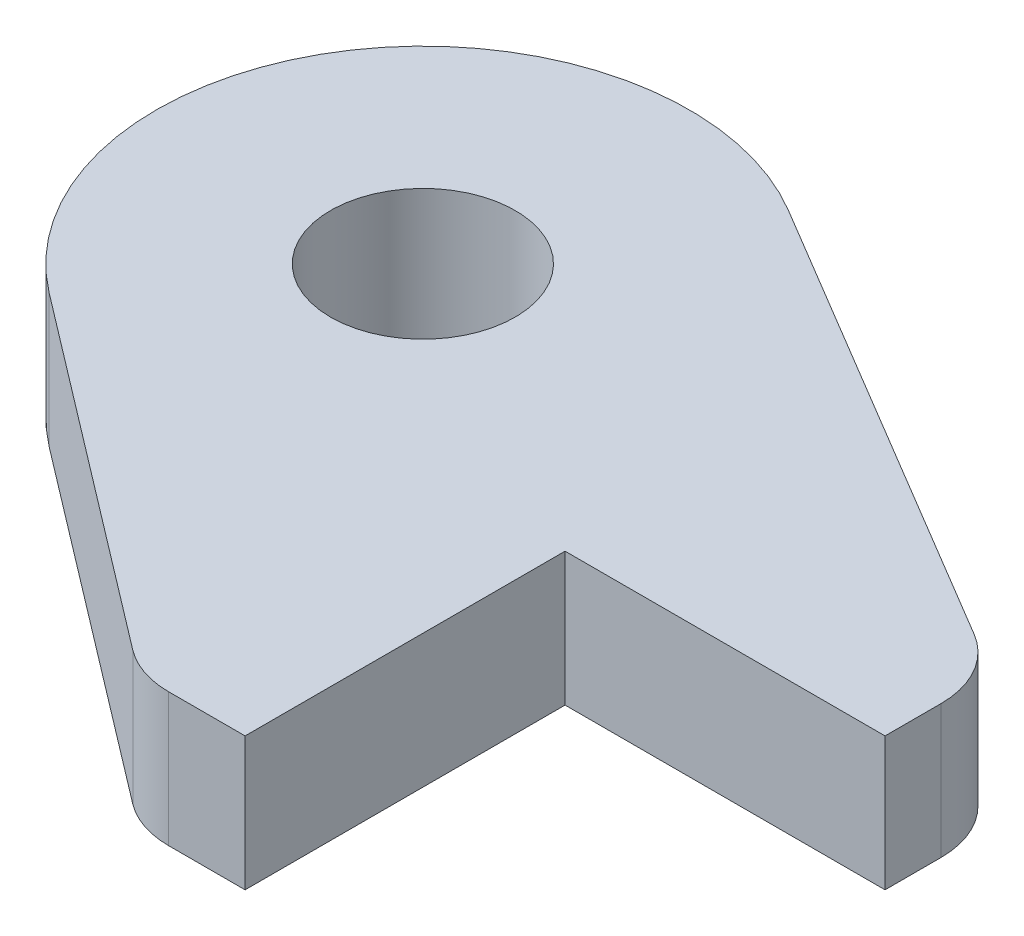
SolidWorks part; units mm, degrees
material "AISI 4130 Steel, annealed at 865C"
ref_plane "X-Y Datum" through (0, 0, 0) normal (0, 0, 1) x (1, 0, 0)
ref_plane "X-Z Datum" through (0, 0, 0) normal (0, 1, 0) x (1, 0, 0)
ref_plane "Y-Z Datum" through (0, 0, 0) normal (1, 0, 0) x (0, 0, -1)
sketch "Sketch1" plane through (0, 0, 0) normal (0, 1, 0) x (1, 0, 0)
  line L0 (-12.7, 12.7) -> (-24.13, 19.05) construction
  line L1 (-12.7, -12.7) -> (12.7, -12.7) construction
  line L2 (-12.7, -12.7) -> (-12.7, 12.7) construction
  line L3 (-12.7, 12.7) -> (12.7, 12.7) construction
  line L4 (12.7, -12.7) -> (12.7, 12.7) construction
  line L5 (-12.7, -12.7) -> (12.7, 12.7) construction
  line L6 (-12.7, 12.7) -> (12.7, -12.7) construction
  line L7 (-19.2522, 27.2313) -> (-1.27, 16.51)
  line L8 (-1.27, 16.51) -> (-1.27, 12.7)
  line L9 (-1.27, 12.7) -> (-12.7, 12.7)
  line L10 (-12.7, 12.7) -> (-12.7, 1.27)
  line L11 (-12.7, 1.27) -> (-16.51, 1.27)
  line L12 (-16.51, 1.27) -> (-29.9024, 11.4734)
  circle A0 centre (-24.13, 19.05) radius 9.525 construction
  arc A1 (-19.2522, 27.2313) -> (-29.9024, 11.4734) centre (-24.13, 19.05) ccw
  point P0 (0, 0)
  dimension "D2" = 19.05
  dimension "D1" = 25.4
  dimension "D3" = 11.43
  dimension "D4" = 6.35
  dimension "D5" = 11.43
  dimension "D6" = 11.43
  dimension "D7" = 3.81
  dimension "D8" = 3.81
extrude "Boss-Extrude1" add sketch "Sketch1" along normal blind 4.7625 contours A1 L12 L11 L10 L9 L8 L7
fillet "Fillet1" radius 3.175 2 edges at (-16.51, 2.3813, -1.27) (-1.27, 2.3813, -16.51)
hole_wizard "M6 Clearance Hole1" positions "Sketch2" profile "Sketch3" hole size "M6" standard "ANSI Metric" end condition through all
sketch "Sketch2" plane through (0, 4.7625, 0) normal (0, 1, 0) x (1, 0, 0)
  point P0 (-24.13, 19.05)
sketch "Sketch3" plane through (-24.13, 4.7625, -19.05) normal (1, 0, 0) x (0, 0, 1)
  line L0 (0, 0) -> (0, 4.7625)
  line L1 (0, 4.7625) -> (3.3, 4.7625)
  line L2 (3.3, 4.7625) -> (3.3, 0)
  line L5 (3.3, 0) -> (0, 0)
  line L11 (0, -6.35) -> (0, 107.95) construction
  dimension "Thru Hole Dia." = 6.6
  dimension "Thru Hole Depth" = 4.7625
